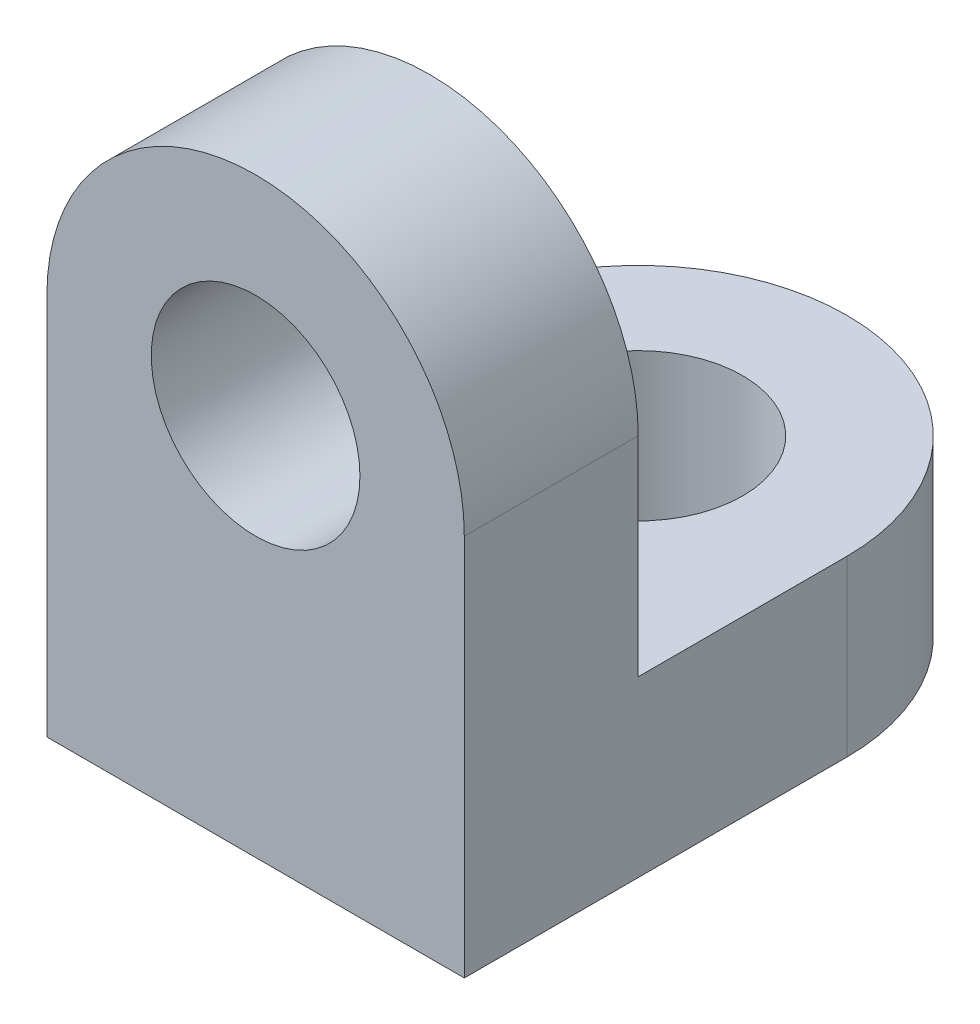
SolidWorks part; units mm, degrees
ref_plane "Front Plane" through (0, 0, 0) normal (0, 0, 1) x (1, 0, 0)
ref_plane "Top Plane" through (0, 0, 0) normal (0, 1, 0) x (1, 0, 0)
ref_plane "Right Plane" through (0, 0, 0) normal (1, 0, 0) x (0, 0, -1)
sketch "Sketch1" plane through (0, 0, 0) normal (0, 0, 1) x (1, 0, 0)
  line L0 (12, 0) -> (12, -12)
  line L1 (12, -12) -> (-12, -12)
  line L2 (-12, -12) -> (-12, 0)
  circle A0 centre (0, 0) radius 6
  arc A1 (12, 0) -> (-12, 0) centre (0, 0) ccw
  point P4 (7.5, 0)
  point P5 (-14.8619, 0.5484)
  dimension "D1" = 12
  dimension "D3" = 12
  dimension "D2" = 24
extrude "Boss-Extrude1" add sketch "Sketch1" along normal blind 10
sketch "Sketch3" plane through (-12, 0, 0) normal (-1, 0, 0) x (0, 0, 1)
  line L0 (0, -12) -> (10, -22)
  line L1 (10, -22) -> (10, -12)
  line L2 (10, -12) -> (0, -12) construction
  line L3 (0, -12) -> (10, -12)
  dimension "D1" = 45
extrude "Boss-Extrude2" add sketch "Sketch3" against normal up to surface (24 mm away) up to face at (12, -6, 5)
mirror "Mirror6" about plane through (26.1421, -12, 0) normal (0, -0.7071, -0.7071) of bodies 103
